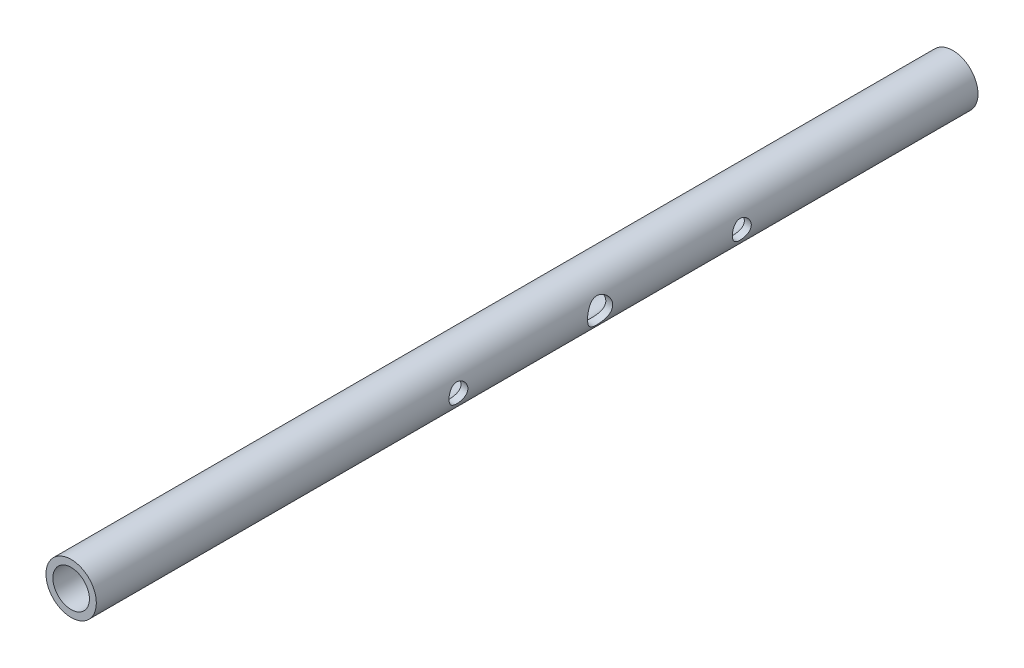
SolidWorks part; units mm, degrees
material "1060 Alloy"
ref_plane "Front Plane" through (0, 0, 0) normal (0, 0, 1) x (1, 0, 0)
ref_plane "Top Plane" through (0, 0, 0) normal (0, 1, 0) x (1, 0, 0)
ref_plane "Right Plane" through (0, 0, 0) normal (1, 0, 0) x (0, 0, -1)
sketch "Sketch1" plane through (0, 0, 0) normal (0, 0, 1) x (1, 0, 0)
  circle A0 centre (0, 0) radius 2.9
  circle A1 centre (0, 0) radius 4
  dimension "D1" = 5.8
  dimension "D2" = 8
extrude "Shaft Boss-Extrude1" add sketch "Sketch1" along normal blind 140
sketch "Sketch2" plane through (0, 0, 0) normal (1, 0, 0) x (0, 0, -1)
  circle A0 centre (-82.5, 0) radius 1.5
  circle A1 centre (-37.5, 0) radius 1.5
  dimension "D1" = 3
  dimension "D2" = 45
  dimension "D3" = 37.5
extrude "PCB Mountinghoples Cut-Extrude1" cut sketch "Sketch2" along normal blind 8.2322 and the other way blind 16
sketch "Sketch3" plane through (0, 0, 0) normal (1, 0, 0) x (0, 0, -1)
  circle A0 centre (-60, 0) radius 2
  circle A1 centre (-37.5, 0) radius 1.5 construction
  dimension "D1" = 22.5
extrude "PCB COnnector Hole Cut-Extrude2" cut sketch "Sketch3" along normal blind 10
